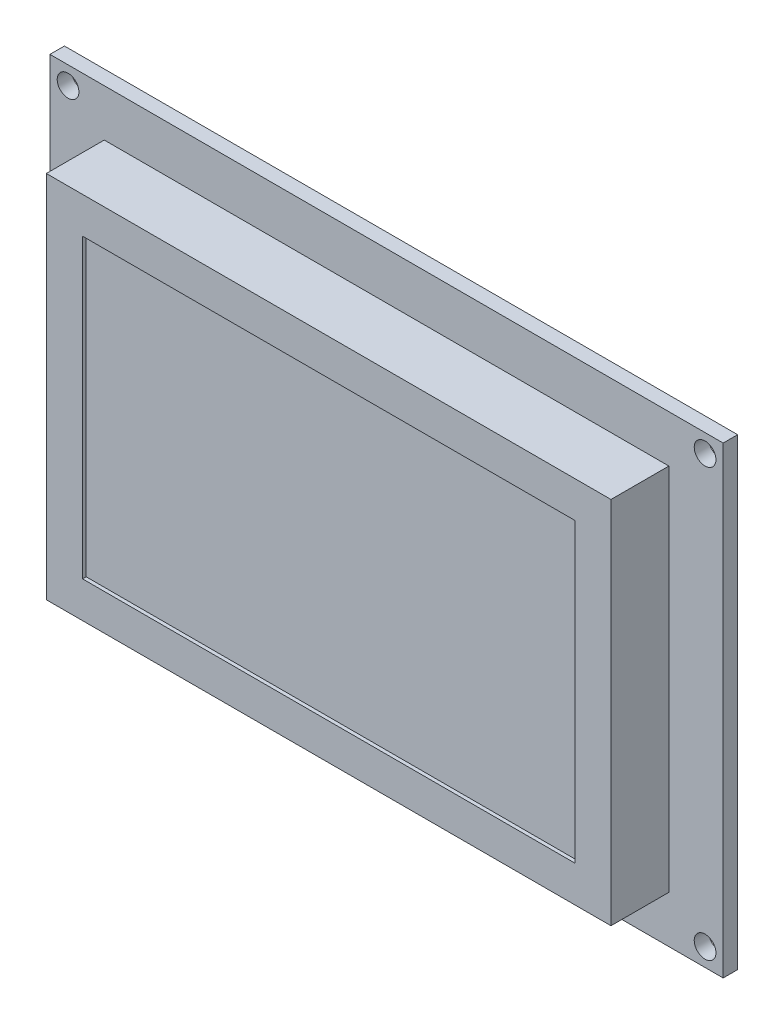
SolidWorks part; units mm, degrees
ref_plane "前视基准面" through (0, 0, 0) normal (0, 0, 1) x (1, 0, 0)
ref_plane "上视基准面" through (0, 0, 0) normal (0, 1, 0) x (1, 0, 0)
ref_plane "右视基准面" through (0, 0, 0) normal (1, 0, 0) x (0, 0, -1)
sketch "草图1" plane through (0, 0, 0) normal (0, 0, 1) x (1, 0, 0)
  line L1 (0, 0) -> (93, 0)
  line L2 (0, 0) -> (0, 64)
  line L3 (0, 64) -> (93, 64)
  line L4 (93, 0) -> (93, 64)
  dimension "D1" = 64
  dimension "D2" = 93
extrude "凸台-拉伸1" add sketch "草图1" along normal blind 2
sketch "草图3" plane through (0, 0, 2) normal (0, 0, 1) x (1, 0, 0)
  line L0 (46.5, 64) -> (46.5, 0) construction
  line L1 (93, 64) -> (0, 64) construction
  line L2 (0, 0) -> (93, 0) construction
  line L3 (0, 32) -> (93, 32) construction
  line L4 (0, 64) -> (0, 0) construction
  line L5 (93, 0) -> (93, 64) construction
  line L7 (7.5, 57.5) -> (85.5, 57.5)
  line L8 (7.5, 57.5) -> (7.5, 6.5)
  line L9 (7.5, 6.5) -> (85.5, 6.5)
  line L10 (85.5, 57.5) -> (85.5, 6.5)
  dimension "D1" = 78
  dimension "D2" = 51
  dimension "D3" = 51
  dimension "D4" = 78
extrude "凸台-拉伸2" add sketch "草图3" along normal blind 8
sketch "草图4" plane through (0, 0, 2) normal (0, 0, 1) x (1, 0, 0)
  line L0 (46.5, 64) -> (46.5, 0) construction
  line L1 (93, 64) -> (0, 64) construction
  line L2 (0, 0) -> (93, 0) construction
  line L3 (0, 32) -> (93, 32) construction
  line L4 (0, 64) -> (0, 0) construction
  line L5 (93, 0) -> (93, 64) construction
  circle A0 centre (2.5, 61.5) radius 1.5
  circle A1 centre (90.5, 61.5) radius 1.5
  circle A2 centre (90.5, 2.5) radius 1.5
  circle A3 centre (2.5, 2.5) radius 1.5
  dimension "D1" = 3
  dimension "D2" = 88
  dimension "D3" = 59
extrude "切除-拉伸1" cut sketch "草图4" against normal through all
sketch "草图5" plane through (0, 0, 10) normal (0, 0, 1) x (1, 0, 0)
  line L8 (12.5, 52.5) -> (12.5, 11.5)
  line L9 (12.5, 11.5) -> (80.5, 11.5)
  line L10 (80.5, 11.5) -> (80.5, 52.5)
  line L11 (80.5, 52.5) -> (12.5, 52.5)
  line L12 (12.5, 52.5) -> (12.5, 11.5)
  line L13 (12.5, 11.5) -> (80.5, 11.5)
  line L14 (80.5, 11.5) -> (80.5, 52.5)
  line L15 (80.5, 52.5) -> (12.5, 52.5)
  dimension "D1" = 5
extrude "切除-拉伸2" cut sketch "草图5" against normal blind 0.5
sketch "草图6" plane through (0, 0, 2) normal (0, 0, 1) x (1, 0, 0)
  line L0 (0, 64) -> (0, 0) construction
  line L1 (0, 0) -> (93, 0) construction
  circle A0 centre (14, 2) radius 0.5
  circle A1 centre (16.54, 2) radius 0.5
  circle A2 centre (19.08, 2) radius 0.5
  circle A3 centre (21.62, 2) radius 0.5
  circle A4 centre (24.16, 2) radius 0.5
  circle A5 centre (26.7, 2) radius 0.5
  circle A6 centre (29.24, 2) radius 0.5
  circle A7 centre (31.78, 2) radius 0.5
  circle A8 centre (34.32, 2) radius 0.5
  circle A9 centre (36.86, 2) radius 0.5
  circle A10 centre (39.4, 2) radius 0.5
  circle A11 centre (41.94, 2) radius 0.5
  circle A12 centre (44.48, 2) radius 0.5
  circle A13 centre (47.02, 2) radius 0.5
  circle A14 centre (49.56, 2) radius 0.5
  circle A15 centre (52.1, 2) radius 0.5
  circle A16 centre (54.64, 2) radius 0.5
  circle A17 centre (57.18, 2) radius 0.5
  circle A18 centre (59.72, 2) radius 0.5
  circle A19 centre (62.26, 2) radius 0.5
  dimension "D1" = 1
  dimension "D3" = 2
  dimension "D2" = 14
  dimension "D4" = 20
extrude "凸台-拉伸3" add sketch "草图6" against normal blind 10
